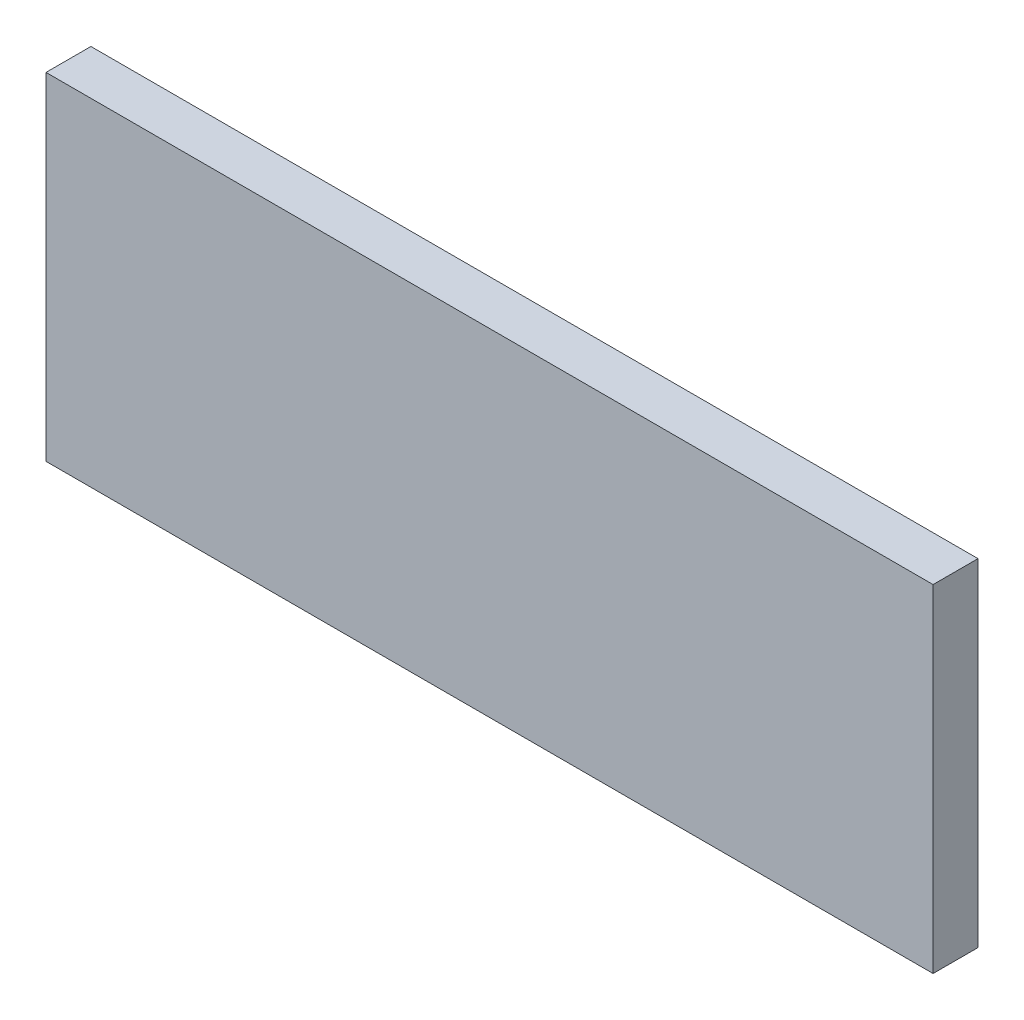
SolidWorks part; units mm, degrees
ref_plane "Front Plane" through (0, 0, 0) normal (0, 0, 1) x (1, 0, 0)
ref_plane "Top Plane" through (0, 0, 0) normal (0, 1, 0) x (1, 0, 0)
ref_plane "Right Plane" through (0, 0, 0) normal (1, 0, 0) x (0, 0, -1)
sketch "Sketch1" plane through (0, 0, 0) normal (0, 0, 1) x (1, 0, 0)
  line L1 (-39.5, -15) -> (39.5, -15)
  line L2 (-39.5, -15) -> (-39.5, 15)
  line L3 (-39.5, 15) -> (39.5, 15)
  line L4 (39.5, -15) -> (39.5, 15)
  line L5 (-39.5, -15) -> (39.5, 15) construction
  line L6 (-39.5, 15) -> (39.5, -15) construction
  point P0 (0, 0)
  dimension "D1" = 79
  dimension "D2" = 30
extrude "Boss-Extrude1" add sketch "Sketch1" along normal blind 4
